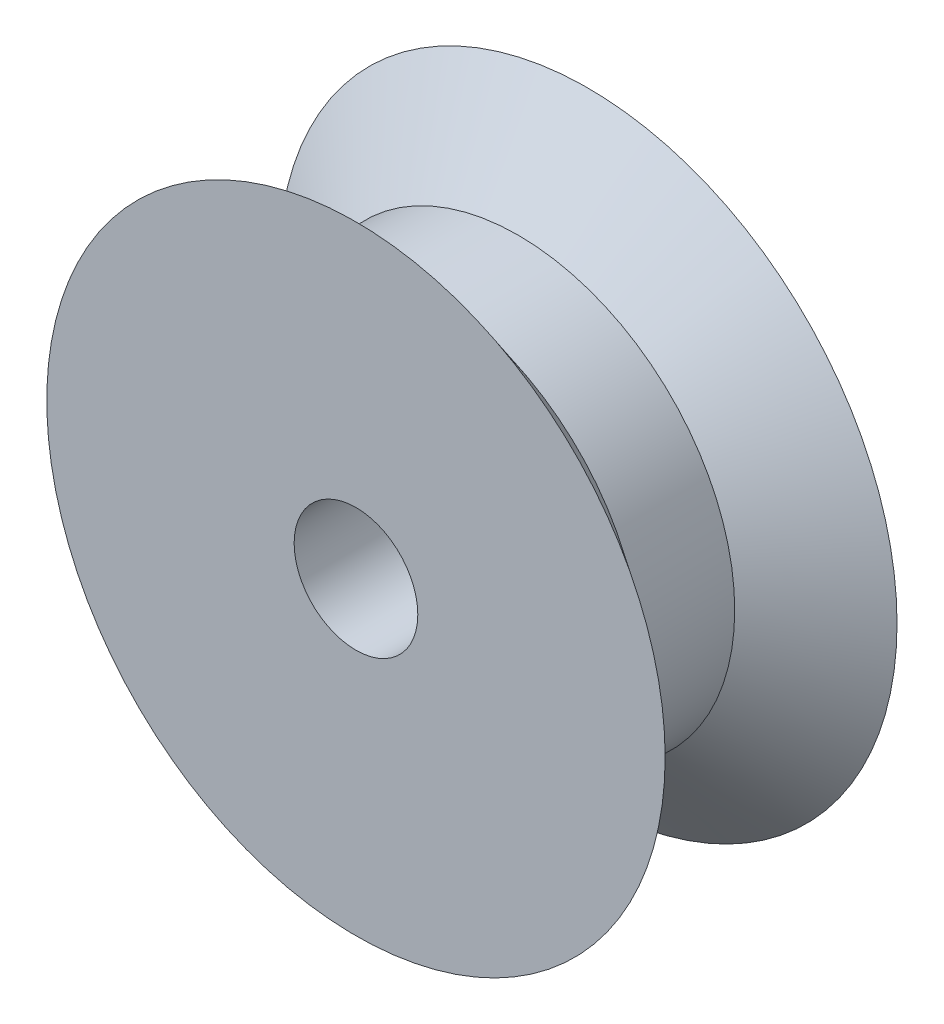
SolidWorks part; units mm, degrees
ref_plane "Front Plane" through (0, 0, 0) normal (0, 0, 1) x (1, 0, 0)
ref_plane "Top Plane" through (0, 0, 0) normal (0, 1, 0) x (1, 0, 0)
ref_plane "Right Plane" through (0, 0, 0) normal (1, 0, 0) x (0, 0, -1)
sketch "Sketch1" plane through (0, 0, 0) normal (0, 0, 1) x (1, 0, 0)
  circle A0 centre (0, 0) radius 5.08
  circle A1 centre (0, 0) radius 25.4
extrude "Boss-Extrude1" add sketch "Sketch1" along normal blind 19.05
sketch "Sketch3" plane through (0, 0, 0) normal (1, 0, 0) x (0, 0, -1)
  line L0 (0, 25.4) -> (0, 34.9117)
  line L1 (0, 34.9117) -> (-19.05, 34.9117)
  line L2 (-19.05, 34.9117) -> (-19.05, 25.4)
  line L3 (-21.0612, 0) -> (0, 0) construction
  line L4 (-19.05, 25.4) -> (-9.525, 25.4) construction
  line L5 (-9.525, 25.4) -> (-9.525, 17.78) construction
  line L6 (-5.715, 17.78) -> (-13.335, 17.78)
  line L7 (-13.335, 17.78) -> (-19.05, 25.4)
  line L8 (-5.715, 17.78) -> (0, 25.4)
revolve "Cut-Revolve1" cut sketch "Sketch3" angle 360 about L3
sketch "Sketch4" plane through (0, 0, 0) normal (0, 0, -1) x (-1, 0, 0)
  circle A0 centre (0, 0) radius 12.7
  circle A1 centre (0, 0) radius 5.08 construction
  circle A2 centre (0, 0) radius 5.08
extrude "Boss-Extrude2" add sketch "Sketch4" along normal blind 6.35
ref_plane "Plane1" through (12.7, 0, 0) normal (1, 0, 0) x (0, 0, -1)
sketch "Sketch5" plane through (12.7, 0, 0) normal (1, 0, 0) x (0, 0, -1)
  line L0 (6.35, -12.7) -> (6.35, 12.7) construction
  circle A0 centre (3.175, 0) radius 1.27
  dimension "D1" = 3.175
extrude "Cut-Extrude1" cut sketch "Sketch5" against normal up to next
sketch "Sketch6" plane through (0, 0, 0) normal (1, 0, 0) x (0, 0, -1)
  line L0 (-9.525, 17.78) -> (-9.525, 26.0186) construction
  line L1 (-5.715, 17.78) -> (-13.335, 17.78) construction
